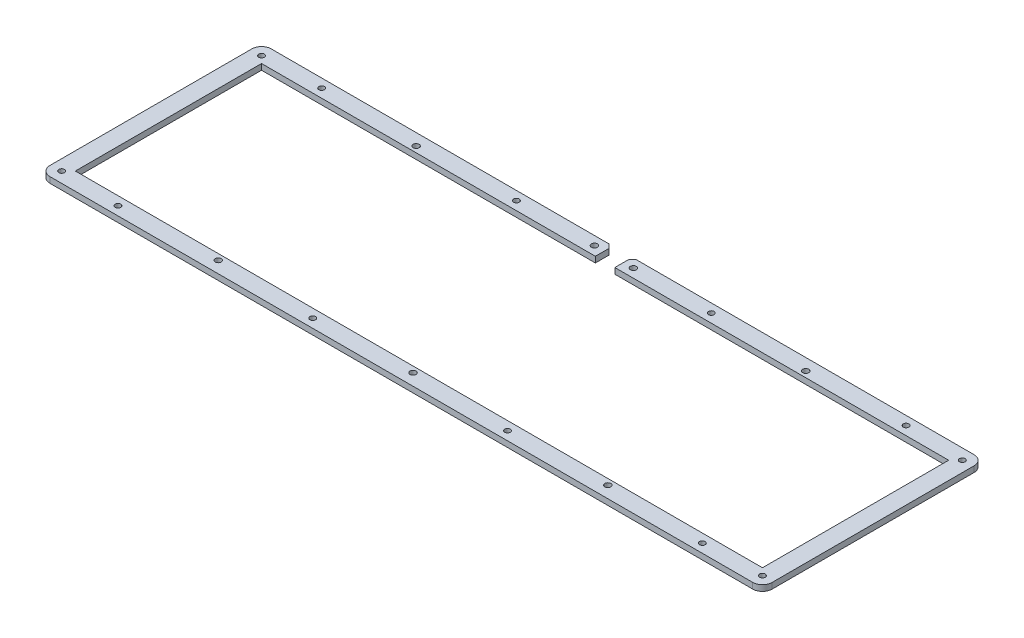
SolidWorks part; units mm, degrees
ref_plane "Front Plane" through (0, 0, 0) normal (0, 0, 1) x (1, 0, 0)
ref_plane "Top Plane" through (0, 0, 0) normal (0, 1, 0) x (1, 0, 0)
ref_plane "Right Plane" through (0, 0, 0) normal (1, 0, 0) x (0, 0, -1)
sketch "Sketch1" plane through (0, 0, 0) normal (0, 1, 0) x (1, 0, 0)
  line L0 (0, 108.6) -> (0, 5)
  line L1 (9, 104.6) -> (9, 9)
  line L2 (365.775, 0) -> (5, 0)
  line L3 (361.775, 9) -> (9, 9)
  line L4 (370.775, 108.6) -> (370.775, 5)
  line L5 (361.775, 104.6) -> (361.775, 9)
  line L6 (180.3875, 104.6) -> (180.3875, 111.6)
  line L7 (180.3875, 111.6) -> (178.3875, 113.6)
  line L8 (190.3875, 111.6) -> (192.3875, 113.6)
  line L9 (190.3875, 104.6) -> (190.3875, 111.6)
  line L10 (9, 104.6) -> (180.3875, 104.6)
  line L11 (5, 113.6) -> (178.3875, 113.6)
  line L12 (190.3875, 104.6) -> (361.775, 104.6)
  line L13 (192.3875, 113.6) -> (365.775, 113.6)
  arc A0 (365.775, 0) -> (370.775, 5) centre (365.775, 5) ccw
  arc A1 (370.775, 108.6) -> (365.775, 113.6) centre (365.775, 108.6) ccw
  arc A2 (0, 5) -> (5, 0) centre (5, 5) ccw
  arc A3 (5, 113.6) -> (0, 108.6) centre (5, 108.6) ccw
  circle A4 centre (35.3875, 4.5) radius 1.45
  circle A5 centre (135.3875, 4.5) radius 1.45
  circle A6 centre (335.3875, 4.5) radius 1.45
  circle A7 centre (235.3875, 4.5) radius 1.45
  circle A8 centre (35.3875, 109.1) radius 1.45
  circle A9 centre (135.3875, 109.1) radius 1.45
  circle A10 centre (335.3875, 109.1) radius 1.45
  circle A11 centre (235.3875, 109.1) radius 1.45
  circle A12 centre (195.3875, 109.1) radius 1.55
  circle A13 centre (175.3875, 109.1) radius 1.55
  circle A14 centre (5.5, 108.1) radius 1.45
  circle A15 centre (5.5, 5.5) radius 1.45
  circle A16 centre (365.275, 5.5) radius 1.45
  circle A17 centre (365.275, 108.1) radius 1.45
  circle A18 centre (85.3875, 107.6) radius 1.55
  circle A19 centre (285.3875, 107.6) radius 1.55
  circle A20 centre (85.3875, 6) radius 1.55
  circle A21 centre (185.3875, 6) radius 1.55
  circle A22 centre (285.3875, 6) radius 1.55
extrude "Boss-Extrude1" add sketch "Sketch1" against normal blind 3
